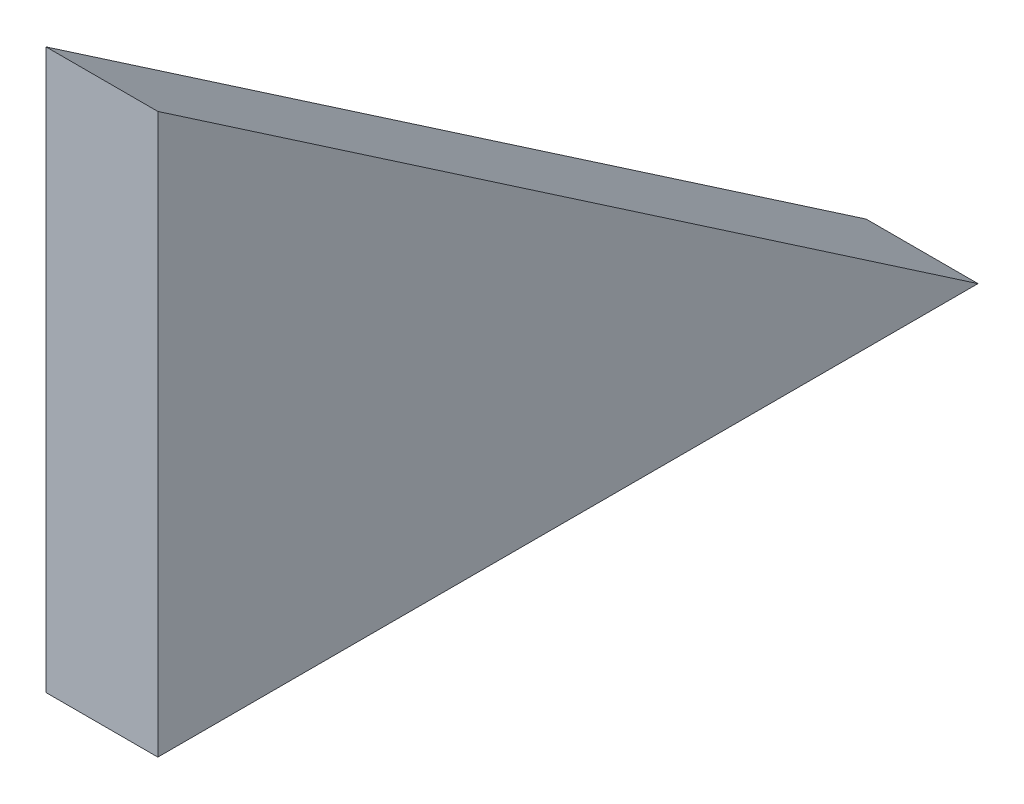
SolidWorks part; units mm, degrees
material "Plain Carbon Steel"
ref_plane "Front Plane" through (0, 0, 0) normal (0, 0, 1) x (1, 0, 0)
ref_plane "Top Plane" through (0, 0, 0) normal (0, 1, 0) x (1, 0, 0)
ref_plane "Right Plane" through (0, 0, 0) normal (1, 0, 0) x (0, 0, -1)
sketch "Sketch1" plane through (0, 0, 0) normal (1, 0, 0) x (0, 0, -1)
  line L0 (0, 9.9873) -> (0, 15)
  line L1 (0, 15) -> (22, 0)
  line L2 (22, 0) -> (0, 0)
  line L3 (0, 0) -> (0, 9.9873)
  dimension "D1" = 22
  dimension "D2" = 15
extrude "Boss-Extrude1" add sketch "Sketch1" along normal blind 3
